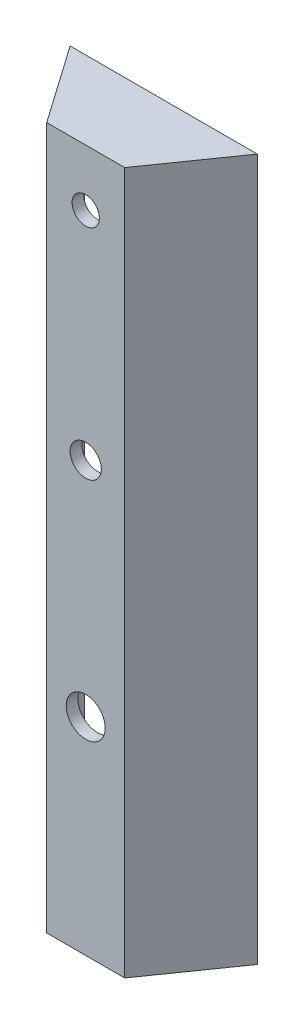
SolidWorks part; units mm, degrees
material "AISI 304"
ref_plane "Front" through (0, 0, 0) normal (0, 0, 1) x (1, 0, 0)
ref_plane "Top" through (0, 0, 0) normal (0, 1, 0) x (1, 0, 0)
ref_plane "Right" through (0, 0, 0) normal (1, 0, 0) x (0, 0, -1)
sketch "Sketch1" plane through (0, 0, 0) normal (0, 1, 0) x (1, 0, 0)
  line L0 (-304.8, 0) -> (304.8, 0)
  line L1 (304.8, 0) -> (127, -254)
  line L2 (127, -254) -> (-127, -254)
  line L3 (-127, -254) -> (-304.8, 0)
  point P4 (0, 0)
  dimension "D1" = 254
  dimension "D2" = 254
  dimension "D3" = 609.6
extrude "Boss-Extrude1" add sketch "Sketch1" along normal blind 2286
shell "Shell3" thickness 38.1
sketch "Sketch2" plane through (0, 0, 254) normal (0, 0, 1) x (1, 0, 0)
  line L0 (0, 2286) -> (0, 0) construction
  line L1 (-127, 2286) -> (127, 2286) construction
  line L2 (-127, 0) -> (127, 0) construction
  circle A0 centre (0, 2101.85) radius 44.45
  circle A1 centre (0, 1397) radius 50.8
  circle A2 centre (0, 673.1) radius 63.5
  dimension "D1" = 88.9
  dimension "D2" = 101.6
  dimension "D3" = 127
  dimension "D5" = 609.6
  dimension "D6" = 609.6
  dimension "D4" = 609.6
extrude "Cut-Extrude1" cut sketch "Sketch2" against normal through all and the other way through all
